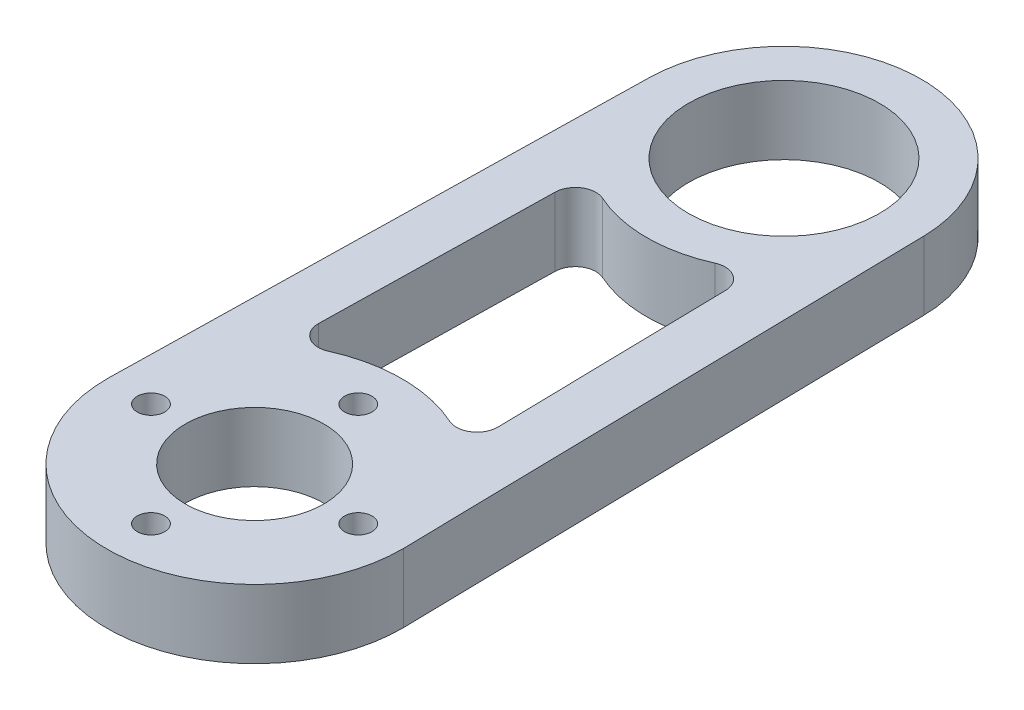
SolidWorks part; units mm, degrees
ref_plane "Front Plane" through (0, 0, 0) normal (0, 0, 1) x (1, 0, 0)
ref_plane "Top Plane" through (0, 0, 0) normal (0, 1, 0) x (1, 0, 0)
ref_plane "Right Plane" through (0, 0, 0) normal (1, 0, 0) x (0, 0, -1)
sketch "Sketch1" plane through (0, 0, 0) normal (0, 1, 0) x (1, 0, 0)
  line L0 (21.499, 0.2091) -> (19.9962, 77.5137)
  line L1 (0, -55) -> (0, 55) construction
  line L2 (-55, 0) -> (55, 0) construction
  line L3 (13.0669, 22.3943) -> (12.4094, 56.1964)
  line L4 (-13.0669, 22.3943) -> (-12.4094, 56.1964)
  line L5 (-21.499, 0.2091) -> (-19.9962, 77.5137)
  circle A1 centre (0, 77.125) radius 13.9135
  arc A2 (-21.499, 0.2091) -> (21.499, 0.2091) centre (0, 0) ccw
  circle A4 centre (0, 15.1) radius 2
  circle A6 centre (15.1, 0) radius 2
  circle A7 centre (0, -15.1) radius 2
  arc A8 (-8.1826, 58.8755) -> (8.1826, 58.8755) centre (0, 77.125) ccw
  arc A9 (-8.8347, 19.601) -> (8.8347, 19.601) centre (0, 0) cw
  circle A10 centre (0, 0) radius 10.1
  arc A13 (13.0669, 22.3943) -> (8.8347, 19.601) centre (10.0675, 22.336) cw
  arc A14 (12.4094, 56.1964) -> (8.1826, 58.8755) centre (9.41, 56.138) ccw
  arc A15 (19.9962, 77.5137) -> (-19.9962, 77.5137) centre (0, 77.125) ccw
  circle A16 centre (-15.1, 0) radius 2
  arc A17 (-13.0669, 22.3943) -> (-8.8347, 19.601) centre (-10.0675, 22.336) ccw
  arc A18 (-12.4094, 56.1964) -> (-8.1826, 58.8755) centre (-9.41, 56.138) cw
  dimension "D1" = 3
extrude "Boss-Extrude1" add sketch "Sketch1" along normal blind 10
